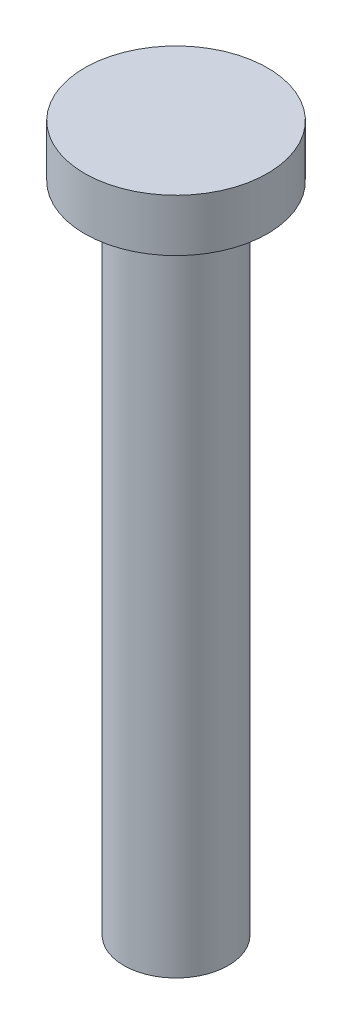
SolidWorks part; units mm, degrees
ref_plane "Plan de face" through (0, 0, 0) normal (0, 0, 1) x (1, 0, 0)
ref_plane "Plan de dessus" through (0, 0, 0) normal (0, 1, 0) x (1, 0, 0)
ref_plane "Plan de droite" through (0, 0, 0) normal (1, 0, 0) x (0, 0, -1)
sketch "Esquisse1" plane through (0, 0, 0) normal (0, 1, 0) x (1, 0, 0)
  circle A0 centre (0, 0) radius 2
  dimension "D1" = 4
extrude "Extrusion1" add sketch "Esquisse1" along normal blind 25
sketch "Esquisse2" plane through (0, 25, 0) normal (0, 1, 0) x (1, 0, 0)
  circle A0 centre (0, 0) radius 3.5
  dimension "D1" = 7
extrude "Extrusion2" add sketch "Esquisse2" along normal blind 2
